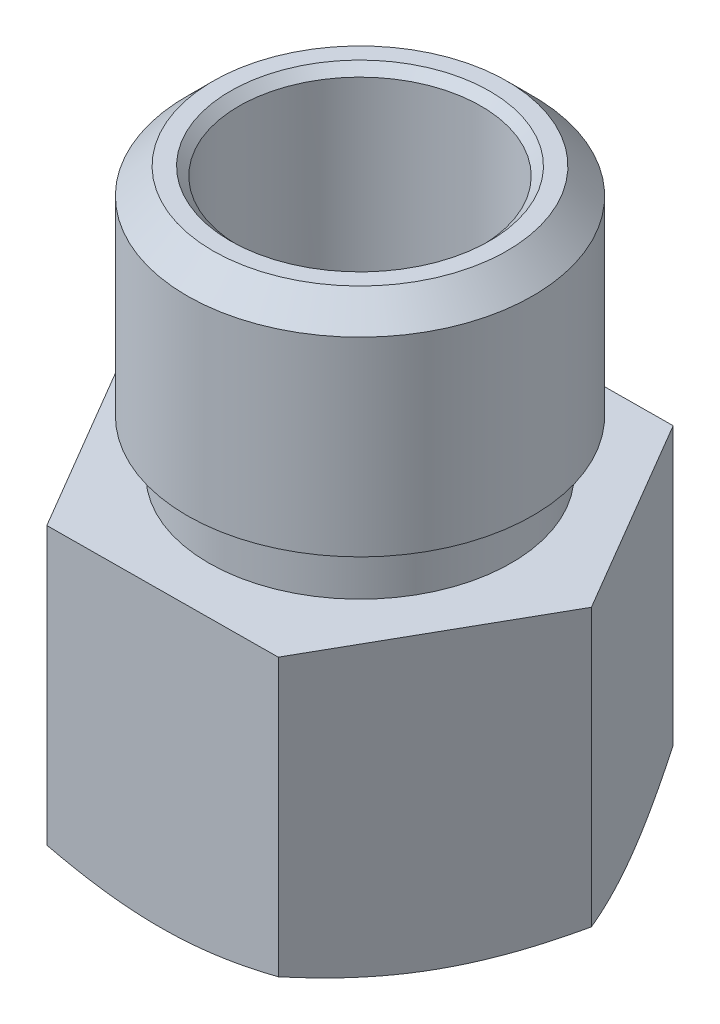
SolidWorks part; units mm, degrees
ref_plane "前视基准面" through (0, 0, 0) normal (0, 0, 1) x (1, 0, 0)
ref_plane "上视基准面" through (0, 0, 0) normal (0, 1, 0) x (1, 0, 0)
ref_plane "右视基准面" through (0, 0, 0) normal (1, 0, 0) x (0, 0, -1)
sketch "草图1" plane through (0, 0, 0) normal (0, 1, 0) x (1, 0, 0)
  line L1 (6.5533, 11.5494) -> (-6.7254, 11.45)
  line L2 (-6.7254, 11.45) -> (-13.2787, -0.0994)
  line L3 (-13.2787, -0.0994) -> (-6.5533, -11.5494)
  line L4 (-6.5533, -11.5494) -> (6.7254, -11.45)
  line L5 (6.7254, -11.45) -> (13.2787, 0.0994)
  line L6 (13.2787, 0.0994) -> (6.5533, 11.5494)
  circle A0 centre (0, 0) radius 11.5 construction
  dimension "D1" = 23
extrude "凸台-拉伸1" add sketch "草图1" along normal blind 17
sketch "草图2" plane through (0, 17, 0) normal (0, 1, 0) x (1, 0, 0)
  circle A0 centre (0, 0) radius 8.75
extrude "凸台-拉伸2" add sketch "草图2" along normal blind 3
sketch "草图3" plane through (0, 20, 0) normal (0, 1, 0) x (1, 0, 0)
  circle A0 centre (0, 0) radius 10
  dimension "D1" = 20
extrude "凸台-拉伸3" add sketch "草图3" along normal blind 12.5 contours A0
cosmetic thread "装饰螺纹线1" parameters "D2"=18.344
chamfer "倒角1" distance 1.5 angle 45 1 edges at (0, 32.5, 10)
ref_plane "基准面1" through (0, 0, 0) normal (0.8697, 0, 0.4935) x (0.4935, 0, -0.8697)
sketch "草图5" plane through (0, 0, 0) normal (0.8697, 0, 0.4935) x (0.4935, 0, -0.8697)
  line L0 (13.2791, 1) -> (11.2791, 0)
  line L1 (13.2791, 17) -> (13.2791, 0) construction
  line L2 (6.6395, 0) -> (13.2791, 0) construction
  line L3 (11.2791, 0) -> (13.2791, 0)
  line L4 (13.2791, 0) -> (13.2791, 1)
  line L5 (0, -1000) -> (0, 49000) construction
  dimension "D1" = 1
  dimension "D2" = 2
revolve "切除-旋转3" cut sketch "草图5" angle 360 about L5
sketch "草图6" plane through (0, 32.5, 0) normal (0, 1, 0) x (1, 0, 0)
  circle A0 centre (0, 0) radius 7
  dimension "D1" = 14
extrude "切除-拉伸1" cut sketch "草图6" against normal through all
chamfer "倒角2" distance 0.5 angle 45 2 edges at (0, 0, 7) (0, 32.5, 7)
sketch "草图7" plane through (0, 0, 0) normal (0, -1, 0) x (1, 0, 0)
  circle A0 centre (0, 0) radius 9.5
  dimension "D1" = 19
extrude "切除-拉伸2" cut sketch "草图7" against normal blind 13
